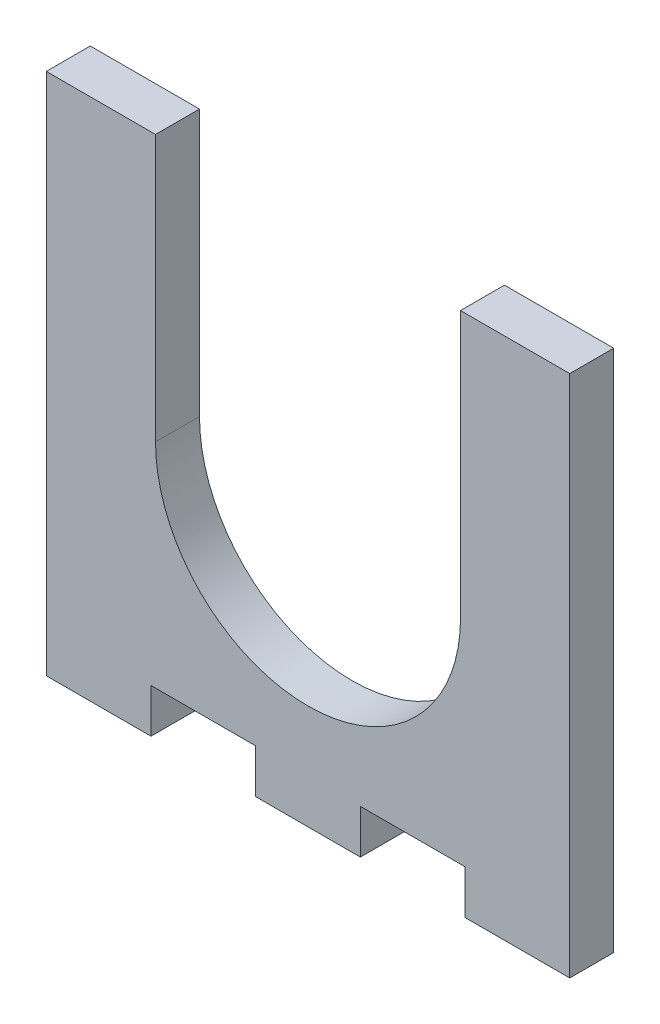
SolidWorks part; units mm, degrees
material "Oak"
ref_plane "Front Plane" through (0, 0, 0) normal (0, 0, 1) x (1, 0, 0)
ref_plane "Top Plane" through (0, 0, 0) normal (0, 1, 0) x (1, 0, 0)
ref_plane "Right Plane" through (0, 0, 0) normal (1, 0, 0) x (0, 0, -1)
sketch "Sketch1" plane through (0, 0, 0) normal (0, 0, 1) x (1, 0, 0)
  line L1 (0, 0) -> (63.5, 0)
  line L2 (0, 0) -> (0, 63.5)
  line L3 (0, 63.5) -> (63.5, 63.5)
  line L4 (63.5, 0) -> (63.5, 63.5)
  dimension "D1" = 63.5
  dimension "D2" = 63.5
extrude "Boss-Extrude1" add sketch "Sketch1" along normal blind 5.334
sketch "Sketch2" plane through (0, 0, 5.334) normal (0, 0, 1) x (1, 0, 0)
  line L0 (0, 0) -> (63.5, 0) construction
  line L1 (12.7, 0) -> (25.4, 0)
  line L2 (12.7, 0) -> (12.7, 5.334)
  line L3 (12.7, 5.334) -> (25.4, 5.334)
  line L4 (25.4, 0) -> (25.4, 5.334)
  line L5 (0, 63.5) -> (0, 0) construction
  line L6 (38.1, 0) -> (50.8, 0)
  line L7 (38.1, 0) -> (38.1, 5.334)
  line L8 (38.1, 5.334) -> (50.8, 5.334)
  line L9 (50.8, 0) -> (50.8, 5.334)
  line L10 (63.5, 0) -> (63.5, 63.5) construction
  line L12 (63.5, 63.5) -> (0, 63.5) construction
  circle A0 centre (31.75, 31.2) radius 18.5
  dimension "D9" = 37
  dimension "D1" = 12.7
  dimension "D2" = 12.7
  dimension "D3" = 5.334
  dimension "D4" = 5.334
  dimension "D5" = 12.7
  dimension "D6" = 12.7
  dimension "D7" = 31.75
  dimension "D8" = 32.3
extrude "Cut-Extrude1" cut sketch "Sketch2" against normal blind 5.334
sketch "Sketch3" plane through (0, 0, 5.334) normal (0, 0, 1) x (1, 0, 0)
  line L0 (63.5, 63.5) -> (0, 63.5) construction
  line L1 (13.25, 31.2) -> (50.25, 31.2)
  line L2 (13.25, 31.2) -> (13.25, 63.5)
  line L3 (13.25, 63.5) -> (50.25, 63.5)
  line L4 (50.25, 31.2) -> (50.25, 63.5)
  circle A0 centre (31.75, 31.2) radius 18.5 construction
extrude "Cut-Extrude2" cut sketch "Sketch3" against normal blind 5.334
equation "\"Base_Width\"= 10in"
equation "\"Base_Length\"= 10in"
equation "\"Wheel_Width\"= 3in"
equation "\"MDF\"= 0.21in"
equation "\"D1@Boss-Extrude1\"=\"MDF\""
equation "\"D3@Sketch2\"=\"MDF\""
equation "\"D4@Sketch2\"=\"MDF\""
equation "\"D1@Cut-Extrude1\"=\"MDF\""
equation "\"D8@Sketch2\"=2in-(37mm/2)"
equation "\"D1@Cut-Extrude2\"=\"MDF\""
